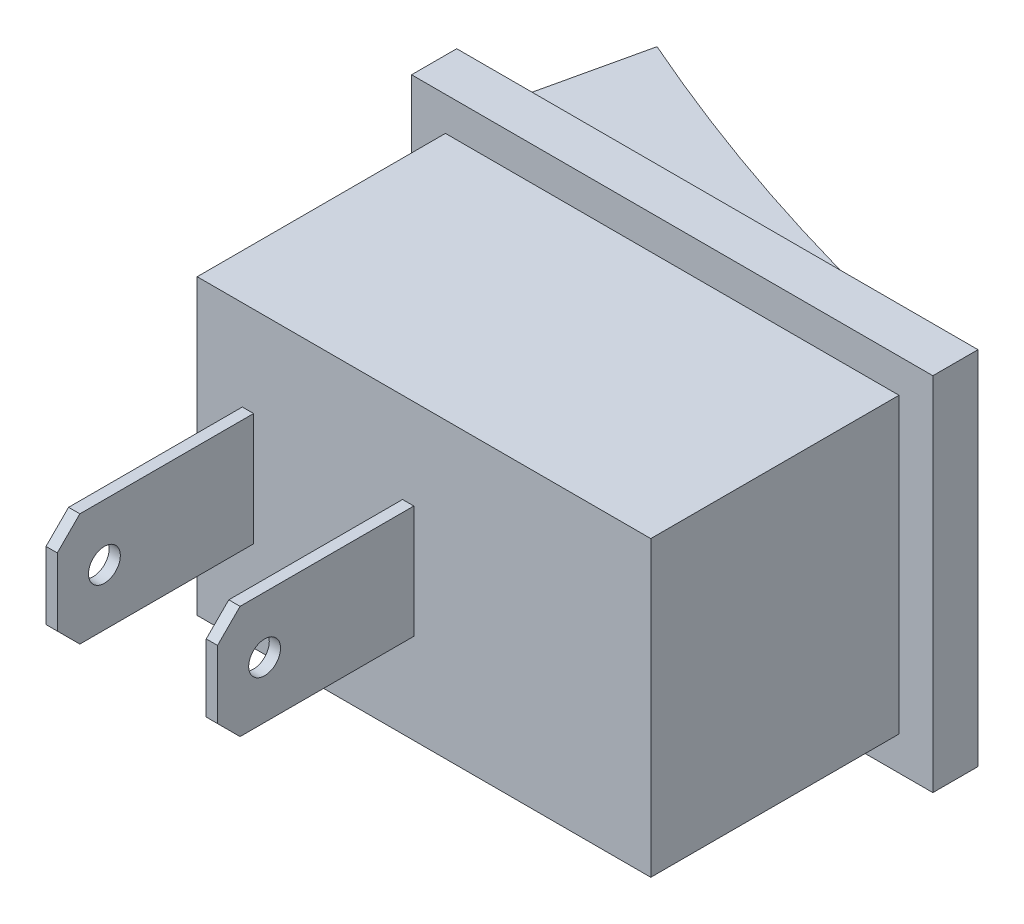
SolidWorks part; units mm, degrees
ref_plane "Ebene vorne" through (0, 0, 0) normal (0, 0, 1) x (1, 0, 0)
ref_plane "Ebene oben" through (0, 0, 0) normal (0, 1, 0) x (1, 0, 0)
ref_plane "Ebene rechts" through (0, 0, 0) normal (1, 0, 0) x (0, 0, -1)
sketch "Skizze1" plane through (0, 0, 0) normal (0, 0, 1) x (1, 0, 0)
  line L1 (0, 0) -> (20.1, 0)
  line L2 (0, 0) -> (0, -13)
  line L3 (0, -13) -> (20.1, -13)
  line L4 (20.1, 0) -> (20.1, -13)
  dimension "D1" = 20.1
  dimension "D2" = 13
extrude "Aufsatz-Linear austragen1" add sketch "Skizze1" along normal blind 11
sketch "Skizze2" plane through (0, 0, 11) normal (0, 0, 1) x (1, 0, 0)
  line L0 (0, -6.5) -> (20.1, -6.5) construction
  line L1 (0, 0) -> (0, -13) construction
  line L2 (20.1, -13) -> (20.1, 0) construction
  line L3 (2, -6.5) -> (2.5, -6.5) construction
  line L4 (2, -4) -> (2.5, -4)
  line L5 (2, -4) -> (2, -9)
  line L6 (2, -9) -> (2.5, -9)
  line L7 (2.5, -4) -> (2.5, -9)
  line L8 (5.8, -4) -> (5.8, -9.002) construction
  line L9 (2, -4) -> (2.5, -4)
  line L10 (2, -9) -> (2.5, -9)
  line L11 (2, -4) -> (2.5, -4)
  line L12 (2, -9) -> (2.5, -9)
  line L13 (2, -4) -> (2.5, -4)
  line L14 (2, -9) -> (2.5, -9)
  line L15 (9.6, -9) -> (9.1, -9)
  line L16 (9.1, -4) -> (9.1, -9)
  line L17 (9.6, -4) -> (9.6, -9)
  line L18 (9.6, -4) -> (9.1, -4)
  dimension "D1" = 0.5
  dimension "D2" = 2
  dimension "D3" = 5
  dimension "D4" = 5.002
  dimension "D5" = 6.6
extrude "Aufsatz-Linear austragen2" add sketch "Skizze2" along normal blind 8.7 contours L7 L4 L5 L6 | L17 L18 L16 L15
sketch "Skizze4" plane through (2, 0, 0) normal (-1, 0, 0) x (0, 0, 1)
  line L0 (19.7, -6.5) -> (11, -6.5) construction
  line L1 (19.7, -4) -> (19.7, -9) construction
  line L2 (11, -4) -> (11, -9) construction
  circle A0 centre (17.6122, -6.5) radius 0.7061
extrude "Schnitt-Linear austragen1" cut sketch "Skizze4" against normal blind 8.7
chamfer "Fase1" distance 1 angle 45 4 edges at (9.35, -9, 19.7) (9.35, -4, 19.7) (2.25, -9, 19.7) (2.25, -4, 19.7)
sketch "Skizze5" plane through (0, 0, 0) normal (0, 0, -1) x (-1, 0, 0)
  line L14 (1.5, -14.5) -> (1.5, 1.5)
  line L15 (-21.6, -14.5) -> (1.5, -14.5)
  line L16 (-21.6, 1.5) -> (-21.6, -14.5)
  line L17 (1.5, 1.5) -> (-21.6, 1.5)
  line L18 (1.5, -14.5) -> (1.5, 1.5)
  line L19 (-21.6, -14.5) -> (1.5, -14.5)
  line L20 (-21.6, 1.5) -> (-21.6, -14.5)
  line L21 (1.5, 1.5) -> (-21.6, 1.5)
  dimension "D1" = 1.5
extrude "Aufsatz-Linear austragen3" add sketch "Skizze5" along normal blind 2
sketch "Skizze6" plane through (0, 0, 0) normal (0, 1, 0) x (1, 0, 0)
  line L0 (0, 2) -> (1.361, 8.0166)
  line L1 (-1.5, 2) -> (21.6, 2) construction
  line L3 (0, 2) -> (20.1, 2)
  arc A0 (1.361, 8.0166) -> (20.1, 2) centre (39.9491, 96.0102) ccw
extrude "Aufsatz-Linear austragen4" add sketch "Skizze6" against normal up to surface (13 mm away) up to face at (10.05, -13, 5.5)
ref_plane "Ebene1" through (10.05, 0, 0) normal (-1, 0, 0) x (0, 0, 1)
